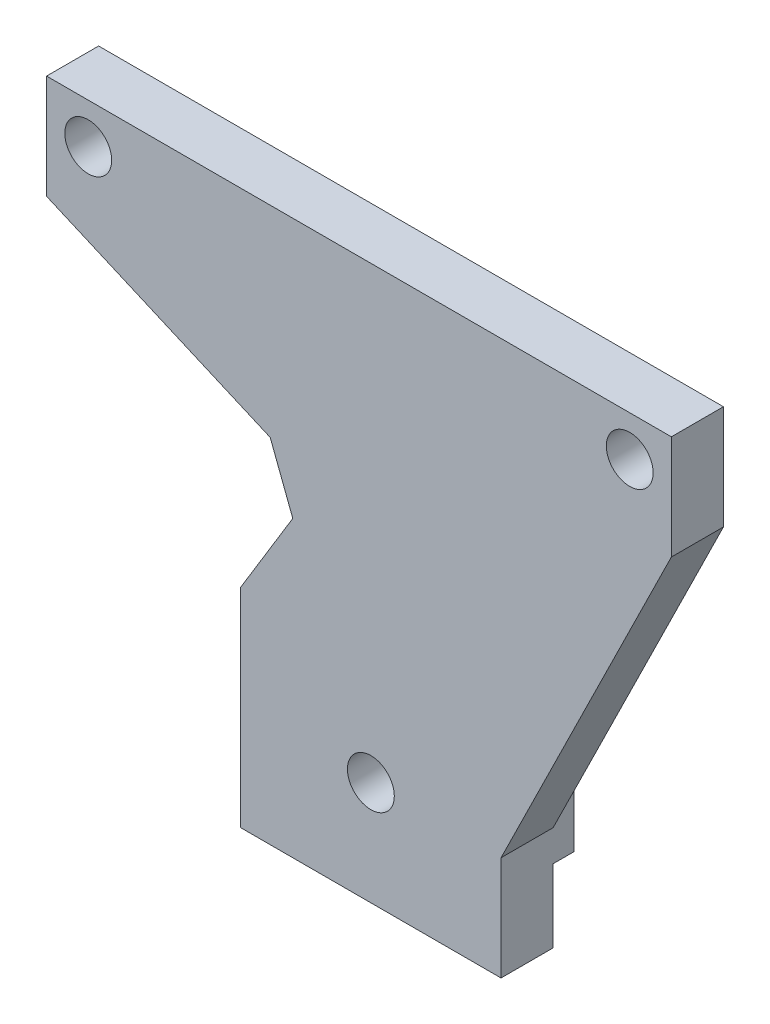
SolidWorks part; units mm, degrees
ref_plane "Plan de face" through (0, 0, 0) normal (0, 0, 1) x (1, 0, 0)
ref_plane "Plan de dessus" through (0, 0, 0) normal (0, 1, 0) x (1, 0, 0)
ref_plane "Plan de droite" through (0, 0, 0) normal (1, 0, 0) x (0, 0, -1)
sketch "Esquisse1" plane through (0, 0, 0) normal (0, 0, 1) x (1, 0, 0)
  line L0 (0, 0) -> (60, 0)
  line L1 (60, 0) -> (60, -10)
  line L2 (0, 0) -> (0, -10)
  line L3 (0, -10) -> (16.3569, -43.1881)
  line L4 (16.3569, -43.1881) -> (16.3569, -53.1881)
  line L5 (16.3569, -53.1881) -> (41.3569, -53.1881)
  line L6 (41.3569, -53.1881) -> (41.3569, -33.1881)
  line L8 (41.3569, -33.1881) -> (36.3557, -24.9678)
  line L9 (36.3557, -24.9678) -> (38.5227, -19.3147)
  line L10 (38.5227, -19.3147) -> (60, -10)
  dimension "D1" = 60
  dimension "D2" = 10
  dimension "D3" = 37
  dimension "D4" = 10
  dimension "D5" = 25
  dimension "D6" = 20
  dimension "D7" = 156.554
  dimension "D8" = 116.237
  dimension "D9" = 82.13
extrude "Boss.-Extru.1" add sketch "Esquisse1" along normal blind 5
sketch "Esquisse2" plane through (0, 0, 0) normal (0, 0, -1) x (-1, 0, 0)
  line L21 (-41.3569, -53.1881) -> (-41.3569, -33.1881) construction
  line L22 (-41.3569, -40.1881) -> (-16.3569, -40.1881)
  line L23 (-41.3569, -40.1881) -> (-41.3569, -46.1881)
  line L24 (-41.3569, -46.1881) -> (-16.3569, -46.1881)
  line L25 (-16.3569, -40.1881) -> (-16.3569, -46.1881)
  line L26 (-16.3569, -43.1881) -> (-16.3569, -53.1881) construction
  line L27 (-16.3569, -53.1881) -> (-41.3569, -53.1881) construction
  dimension "D4" = 6
  dimension "D5" = 7
extrude "Boss.-Extru.2" add sketch "Esquisse2" along normal blind 2
sketch "Esquisse3" plane through (0, 0, -2) normal (0, 0, -1) x (-1, 0, 0)
  line L0 (-56, -3.88) -> (-4, -3.88) construction
  line L2 (-60, -10) -> (-60, 0) construction
  line L4 (-60, 0) -> (0, 0) construction
  line L9 (-16.3569, -53.1881) -> (-41.3569, -53.1881) construction
  circle A3 centre (-28.8569, -43.1881) radius 2.25
  circle A4 centre (-56, -3.88) radius 2.25
  circle A5 centre (-4, -3.88) radius 2.25
  dimension "D3" = 4
  dimension "D6" = 4.5
  dimension "D1" = 4.5
  dimension "D2" = 52
  dimension "D4" = 3.88
  dimension "D7" = 10
extrude "Enlèv. mat.-Extru.3" cut sketch "Esquisse3" against normal blind 8.1
mirror "Symétrie1" about plane through (0, 0, 5) normal (1, 0, 0) of bodies 103
ref_plane "Plan1" through (0, 0, 0) normal (-1, 0, 0) x (0, 0, 1)
split "Fractionner1" trim tools "Plan1" bodies to split 104 resulting bodies 106
